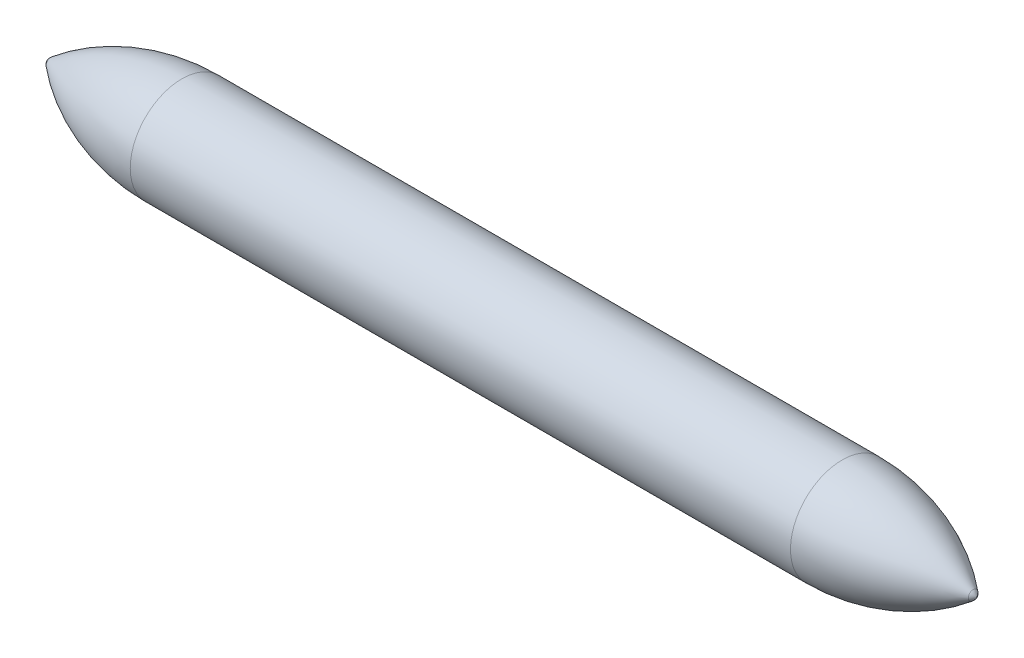
SolidWorks part; units mm, degrees
material "PVC Rigid"
ref_plane "Frontal" through (0, 0, 0) normal (0, 0, 1) x (1, 0, 0)
ref_plane "Superior" through (0, 0, 0) normal (0, 1, 0) x (1, 0, 0)
ref_plane "Lateral" through (0, 0, 0) normal (1, 0, 0) x (0, 0, -1)
sketch "Sketch1" plane through (0, 0, 0) normal (0, 0, 1) x (1, 0, 0)
  line L0 (-10.9022, 0) -> (25.2002, 0) construction
  line L1 (2.6071, 1) -> (15.3923, 1)
  line L2 (0, 0) -> (18, 0)
  arc A0 (17.9293, 0.0934) -> (15.3923, 1) centre (15.3923, -3.0029) ccw
  arc A1 (2.6071, 1) -> (0.0707, 0.0934) centre (2.6071, -3.0012) ccw
  arc A2 (18, 0) -> (17.9293, 0.0934) centre (17.7709, -0.1) ccw
  arc A3 (0.0707, 0.0934) -> (0, 0) centre (0.2291, -0.1) ccw
  dimension "D1" = 4.0029
  dimension "D3" = 4.0012
  dimension "D5" = 18
  dimension "D4" = 0.5
  dimension "D6" = 0.25
  dimension "D7" = 0.1
  dimension "D8" = 0.1
  dimension "D2" = 1
revolve "Base-Revolve" add sketch "Sketch1" angle 360 about L0
